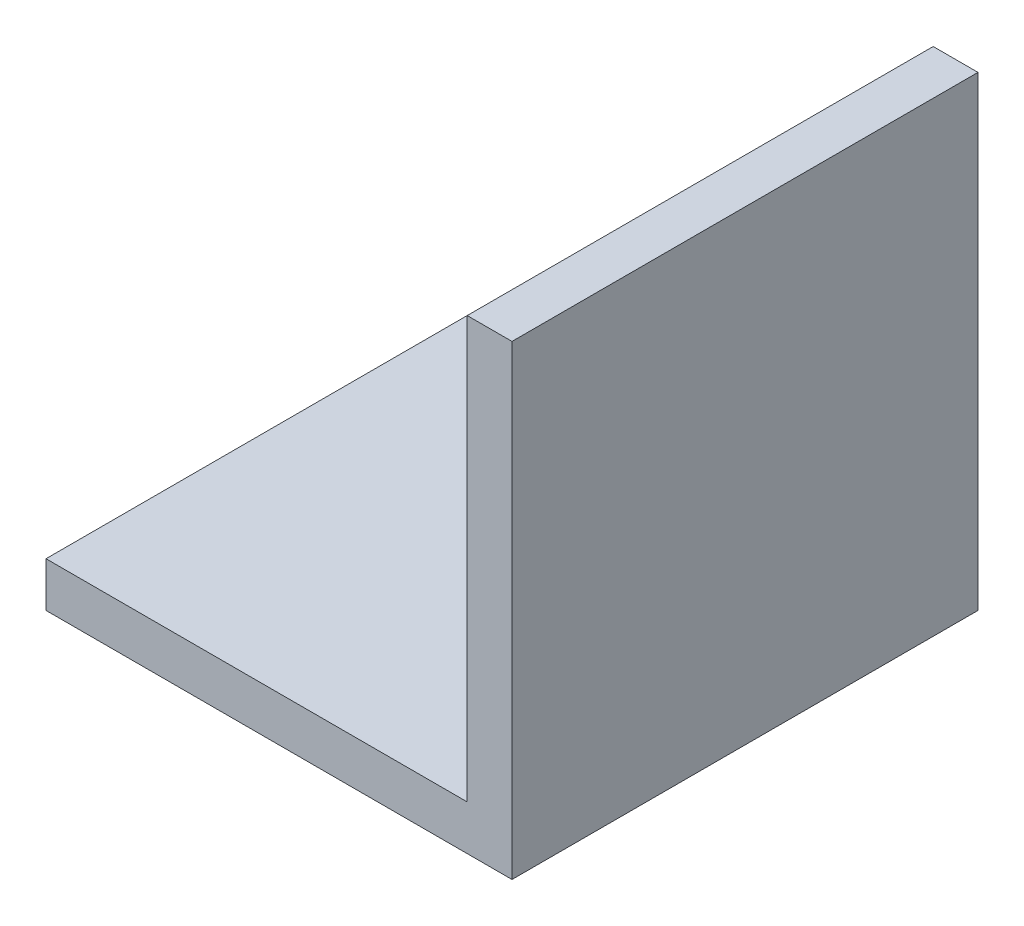
SolidWorks part; units mm, degrees
ref_plane "Front Plane" through (0, 0, 0) normal (0, 0, 1) x (1, 0, 0)
ref_plane "Top Plane" through (0, 0, 0) normal (0, 1, 0) x (1, 0, 0)
ref_plane "Right Plane" through (0, 0, 0) normal (1, 0, 0) x (0, 0, -1)
sketch "Sketch1" plane through (0, 0, 0) normal (0, 0, 1) x (1, 0, 0)
  line L0 (-28.8799, -5.5417) -> (12.3951, -5.5417)
  line L1 (-28.8799, -1.573) -> (8.4263, -1.573)
  line L2 (-28.8799, -1.573) -> (-28.8799, -5.5417)
  line L6 (12.3951, -5.5417) -> (12.3951, 35.7333)
  line L7 (12.3951, 35.7333) -> (8.4263, 35.7333)
  line L8 (8.4263, -1.573) -> (8.4263, 35.7333)
  dimension "D1" = 41.275
  dimension "D2" = 41.275
  dimension "D3" = 3.9688
  dimension "D4" = 3.9688
extrude "Boss-Extrude1" add sketch "Sketch1" along normal blind 41.275
